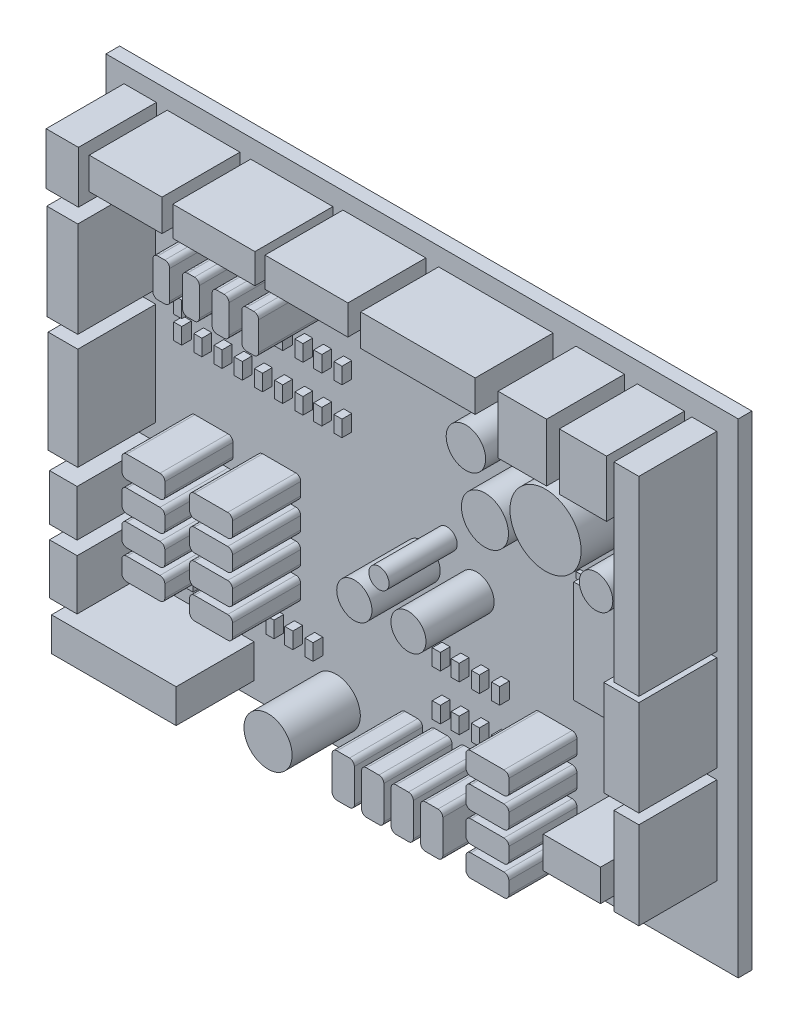
SolidWorks part; units mm, degrees
ref_plane "Plan de face" through (0, 0, 0) normal (0, 0, 1) x (1, 0, 0)
ref_plane "Plan de dessus" through (0, 0, 0) normal (0, 1, 0) x (1, 0, 0)
ref_plane "Plan de droite" through (0, 0, 0) normal (1, 0, 0) x (0, 0, -1)
sketch "Esquisse1" plane through (0, 0, 0) normal (0, 0, 1) x (1, 0, 0)
  line L1 (0, 0) -> (64.9, 0)
  line L2 (0, 0) -> (0, 49.7)
  line L3 (0, 49.7) -> (64.9, 49.7)
  line L4 (64.9, 0) -> (64.9, 49.7)
  dimension "D1" = 64.9
  dimension "D2" = 49.7
extrude "Extrusion1" add sketch "Esquisse1" along normal blind 1.4
sketch "Esquisse2" plane through (0, 0, 1.4) normal (0, 0, 1) x (1, 0, 0)
  line L1 (1.8564, 47.9767) -> (5.175, 47.9767)
  line L2 (1.8564, 47.9767) -> (1.8564, 42.6531)
  line L3 (1.8564, 42.6531) -> (5.175, 42.6531)
  line L4 (5.175, 47.9767) -> (5.175, 42.6531)
  line L5 (24.3263, 47.9767) -> (32.8303, 47.9767)
  line L6 (24.3263, 47.9767) -> (24.3263, 44.9346)
  line L7 (24.3263, 44.9346) -> (32.8303, 44.9346)
  line L8 (32.8303, 47.9767) -> (32.8303, 44.9346)
extrude "Extrusion2" add sketch "Esquisse2" along normal blind 8
sketch "Esquisse3" plane through (0, 0, 1.4) normal (0, 0, 1) x (1, 0, 0)
  line L1 (6.2812, 47.8384) -> (13.7481, 47.8384)
  line L2 (6.2812, 47.8384) -> (6.2812, 44.5889)
  line L3 (6.2812, 44.5889) -> (13.7481, 44.5889)
  line L4 (13.7481, 47.8384) -> (13.7481, 44.5889)
  line L5 (1.9255, 41.132) -> (5.1059, 41.132)
  line L6 (1.9255, 41.132) -> (1.9255, 31.3144)
  line L7 (1.9255, 31.3144) -> (5.1059, 31.3144)
  line L8 (5.1059, 41.132) -> (5.1059, 31.3144)
  line L9 (34.1439, 47.8384) -> (45.8974, 47.8384)
  line L10 (34.1439, 47.8384) -> (34.1439, 44.5889)
  line L11 (34.1439, 44.5889) -> (45.8974, 44.5889)
  line L12 (45.8974, 47.8384) -> (45.8974, 44.5889)
  line L13 (48.2481, 47.8384) -> (53.226, 47.8384)
  line L14 (48.2481, 47.8384) -> (48.2481, 41.8926)
  line L15 (48.2481, 41.8926) -> (53.226, 41.8926)
  line L16 (53.226, 47.8384) -> (53.226, 41.8926)
extrude "Extrusion3" add sketch "Esquisse3" along normal blind 8
sketch "Esquisse4" plane through (0, 0, 1.4) normal (0, 0, 1) x (1, 0, 0)
  line L1 (14.8543, 47.7693) -> (23.2892, 47.7693)
  line L2 (14.8543, 47.7693) -> (14.8543, 44.7272)
  line L3 (14.8543, 44.7272) -> (23.2892, 44.7272)
  line L4 (23.2892, 47.7693) -> (23.2892, 44.7272)
  line L5 (2.0638, 30.0008) -> (5.1059, 30.0008)
  line L6 (2.0638, 30.0008) -> (2.0638, 19.4918)
  line L7 (2.0638, 19.4918) -> (5.1059, 19.4918)
  line L8 (5.1059, 30.0008) -> (5.1059, 19.4918)
  line L9 (59.1028, 17.5559) -> (62.6979, 17.5559)
  line L10 (59.1028, 17.5559) -> (59.1028, 27.3735)
  line L11 (59.1028, 27.3735) -> (62.6979, 27.3735)
  line L12 (62.6979, 17.5559) -> (62.6979, 27.3735)
extrude "Extrusion4" add sketch "Esquisse4" along normal blind 8
sketch "Esquisse5" plane through (0, 0, 1.4) normal (0, 0, 1) x (1, 0, 0)
  line L1 (2.2021, 17.7633) -> (5.0367, 17.7633)
  line L2 (2.2021, 17.7633) -> (2.2021, 12.9928)
  line L3 (2.2021, 12.9928) -> (5.0367, 12.9928)
  line L4 (5.0367, 17.7633) -> (5.0367, 12.9928)
  line L5 (54.5396, 47.631) -> (59.3793, 47.631)
  line L6 (54.5396, 47.631) -> (54.5396, 41.8234)
  line L7 (54.5396, 41.8234) -> (59.3793, 41.8234)
  line L8 (59.3793, 47.631) -> (59.3793, 41.8234)
extrude "Extrusion5" add sketch "Esquisse5" along normal blind 8
sketch "Esquisse6" plane through (0, 0, 1.4) normal (0, 0, 1) x (1, 0, 0)
  line L1 (2.2021, 11.61) -> (5.0367, 11.61)
  line L2 (2.2021, 11.61) -> (2.2021, 6.4247)
  line L3 (2.2021, 6.4247) -> (5.0367, 6.4247)
  line L4 (5.0367, 11.61) -> (5.0367, 6.4247)
extrude "Extrusion6" add sketch "Esquisse6" along normal blind 8
sketch "Esquisse7" plane through (0, 0, 1.4) normal (0, 0, 1) x (1, 0, 0)
  line L1 (60.1398, 47.4928) -> (62.6979, 47.4928)
  line L2 (60.1398, 47.4928) -> (60.1398, 27.9266)
  line L3 (60.1398, 27.9266) -> (62.6979, 27.9266)
  line L4 (62.6979, 47.4928) -> (62.6979, 27.9266)
  line L5 (62.6979, 16.5189) -> (60.1398, 16.5189)
  line L6 (62.6979, 16.5189) -> (62.6979, 7.5309)
  line L7 (62.6979, 7.5309) -> (60.1398, 7.5309)
  line L8 (60.1398, 16.5189) -> (60.1398, 7.5309)
  line L9 (58.7571, 10.7804) -> (52.8803, 10.7804)
  line L10 (58.7571, 10.7804) -> (58.7571, 7.5309)
  line L11 (58.7571, 7.5309) -> (52.8803, 7.5309)
  line L12 (52.8803, 10.7804) -> (52.8803, 7.5309)
  line L13 (2.4095, 5.0419) -> (15.2, 5.0419)
  line L14 (2.4095, 5.0419) -> (2.4095, 1.585)
  line L15 (2.4095, 1.585) -> (15.2, 1.585)
  line L16 (15.2, 5.0419) -> (15.2, 1.585)
extrude "Extrusion7" add sketch "Esquisse7" along normal blind 8
sketch "Esquisse8" plane through (0, 0, 1.4) normal (0, 0, 1) x (1, 0, 0)
  line L0 (15.3543, 41.3926) -> (16.0828, 41.3926)
  line L1 (12.3123, 41.3926) -> (13.0407, 41.3926)
  line L2 (11.8123, 40.8926) -> (11.8123, 37.9837)
  line L3 (12.3123, 37.4837) -> (13.0407, 37.4837)
  line L4 (13.5407, 40.8926) -> (13.5407, 37.9837)
  line L5 (15.3543, 37.4837) -> (16.0828, 37.4837)
  line L6 (14.8543, 40.8926) -> (14.8543, 37.9837)
  line L7 (16.5828, 40.8926) -> (16.5828, 37.9837)
  line L8 (18.3964, 41.3926) -> (19.1249, 41.3926)
  line L9 (18.3964, 37.4837) -> (19.1249, 37.4837)
  line L10 (17.8964, 40.8926) -> (17.8964, 37.9837)
  line L11 (19.6249, 40.8926) -> (19.6249, 37.9837)
  line L12 (21.4385, 41.3926) -> (22.1669, 41.3926)
  line L13 (21.4385, 37.4837) -> (22.1669, 37.4837)
  line L14 (20.9385, 40.8926) -> (20.9385, 37.9837)
  line L15 (22.6669, 40.8926) -> (22.6669, 37.9837)
  line L16 (8.6319, 18.6621) -> (8.6319, 17.3806)
  line L17 (9.1319, 22.1882) -> (12.5407, 22.1882)
  line L18 (8.6319, 21.6882) -> (8.6319, 20.4066)
  line L19 (9.1319, 19.9066) -> (12.5407, 19.9066)
  line L20 (13.0407, 21.6882) -> (13.0407, 20.4066)
  line L21 (9.1319, 19.1621) -> (12.5407, 19.1621)
  line L22 (9.1319, 16.8806) -> (12.5407, 16.8806)
  line L23 (13.0407, 18.6621) -> (13.0407, 17.3806)
  line L24 (8.6319, 15.6361) -> (8.6319, 14.3545)
  line L25 (9.1319, 16.1361) -> (12.5407, 16.1361)
  line L26 (9.1319, 13.8545) -> (12.5407, 13.8545)
  line L27 (13.0407, 15.6361) -> (13.0407, 14.3545)
  line L28 (8.6319, 12.61) -> (8.6319, 11.3285)
  line L29 (9.1319, 13.11) -> (12.5407, 13.11)
  line L30 (9.1319, 10.8285) -> (12.5407, 10.8285)
  line L31 (13.0407, 12.61) -> (13.0407, 11.3285)
  line L32 (16.0828, 19.1621) -> (19.4916, 19.1621)
  line L33 (16.0828, 13.11) -> (19.4916, 13.11)
  line L34 (19.9916, 21.6882) -> (19.9916, 20.4066)
  line L35 (16.0828, 16.8806) -> (19.4916, 16.8806)
  line L36 (16.0828, 10.8285) -> (19.4916, 10.8285)
  line L37 (15.5828, 21.6882) -> (15.5828, 20.4066)
  line L38 (15.5828, 12.61) -> (15.5828, 11.3285)
  line L39 (19.9916, 12.61) -> (19.9916, 11.3285)
  line L40 (15.5828, 18.6621) -> (15.5828, 17.3806)
  line L41 (15.5828, 15.6361) -> (15.5828, 14.3545)
  line L42 (16.0828, 16.1361) -> (19.4916, 16.1361)
  line L43 (16.0828, 13.8545) -> (19.4916, 13.8545)
  line L44 (16.0828, 19.9066) -> (19.4916, 19.9066)
  line L45 (19.9916, 15.6361) -> (19.9916, 14.3545)
  line L46 (16.0828, 22.1882) -> (19.4916, 22.1882)
  line L47 (19.9916, 18.6621) -> (19.9916, 17.3806)
  line L48 (33.2391, 2.6942) -> (33.2391, 6.103)
  line L49 (39.2912, 2.6942) -> (39.2912, 6.103)
  line L50 (30.713, 6.603) -> (31.9946, 6.603)
  line L51 (35.5206, 2.6942) -> (35.5206, 6.103)
  line L52 (41.5727, 2.6942) -> (41.5727, 6.103)
  line L53 (30.713, 2.1942) -> (31.9946, 2.1942)
  line L54 (39.7912, 2.1942) -> (41.0727, 2.1942)
  line L55 (39.7912, 6.603) -> (41.0727, 6.603)
  line L56 (33.7391, 2.1942) -> (35.0206, 2.1942)
  line L57 (36.7651, 2.1942) -> (38.0467, 2.1942)
  line L58 (36.2651, 2.6942) -> (36.2651, 6.103)
  line L59 (38.5467, 2.6942) -> (38.5467, 6.103)
  line L60 (32.4946, 2.6942) -> (32.4946, 6.103)
  line L61 (36.7651, 6.603) -> (38.0467, 6.603)
  line L62 (30.213, 2.6942) -> (30.213, 6.103)
  line L63 (33.7391, 6.603) -> (35.0206, 6.603)
  line L64 (44.4455, 10.4507) -> (47.8543, 10.4507)
  line L65 (44.4455, 4.3986) -> (47.8543, 4.3986)
  line L66 (48.3543, 12.9768) -> (48.3543, 11.6952)
  line L67 (44.4455, 8.1692) -> (47.8543, 8.1692)
  line L68 (44.4455, 2.1171) -> (47.8543, 2.1171)
  line L69 (43.9455, 12.9768) -> (43.9455, 11.6952)
  line L70 (43.9455, 3.8986) -> (43.9455, 2.6171)
  line L71 (48.3543, 3.8986) -> (48.3543, 2.6171)
  line L72 (43.9455, 9.9507) -> (43.9455, 8.6692)
  line L73 (43.9455, 6.9247) -> (43.9455, 5.6431)
  line L74 (44.4455, 7.4247) -> (47.8543, 7.4247)
  line L75 (44.4455, 5.1431) -> (47.8543, 5.1431)
  line L76 (44.4455, 11.1952) -> (47.8543, 11.1952)
  line L77 (48.3543, 6.9247) -> (48.3543, 5.6431)
  line L78 (44.4455, 13.4768) -> (47.8543, 13.4768)
  line L79 (48.3543, 9.9507) -> (48.3543, 8.6692)
  arc A0 (12.3123, 41.3926) -> (11.8123, 40.8926) centre (12.3123, 40.8926) ccw
  arc A1 (13.0407, 41.3926) -> (13.5407, 40.8926) centre (13.0407, 40.8926) cw
  arc A2 (13.0407, 37.4837) -> (13.5407, 37.9837) centre (13.0407, 37.9837) ccw
  arc A3 (11.8123, 37.9837) -> (12.3123, 37.4837) centre (12.3123, 37.9837) ccw
  arc A4 (14.8543, 37.9837) -> (15.3543, 37.4837) centre (15.3543, 37.9837) ccw
  arc A5 (15.3543, 41.3926) -> (14.8543, 40.8926) centre (15.3543, 40.8926) ccw
  arc A6 (16.0828, 41.3926) -> (16.5828, 40.8926) centre (16.0828, 40.8926) cw
  arc A7 (16.0828, 37.4837) -> (16.5828, 37.9837) centre (16.0828, 37.9837) ccw
  arc A8 (17.8964, 37.9837) -> (18.3964, 37.4837) centre (18.3964, 37.9837) ccw
  arc A9 (18.3964, 41.3926) -> (17.8964, 40.8926) centre (18.3964, 40.8926) ccw
  arc A10 (19.1249, 41.3926) -> (19.6249, 40.8926) centre (19.1249, 40.8926) cw
  arc A11 (19.1249, 37.4837) -> (19.6249, 37.9837) centre (19.1249, 37.9837) ccw
  arc A12 (20.9385, 37.9837) -> (21.4385, 37.4837) centre (21.4385, 37.9837) ccw
  arc A13 (21.4385, 41.3926) -> (20.9385, 40.8926) centre (21.4385, 40.8926) ccw
  arc A14 (22.1669, 41.3926) -> (22.6669, 40.8926) centre (22.1669, 40.8926) cw
  arc A15 (22.1669, 37.4837) -> (22.6669, 37.9837) centre (22.1669, 37.9837) ccw
  arc A16 (9.1319, 22.1882) -> (8.6319, 21.6882) centre (9.1319, 21.6882) ccw
  arc A17 (8.6319, 20.4066) -> (9.1319, 19.9066) centre (9.1319, 20.4066) ccw
  arc A18 (12.5407, 19.9066) -> (13.0407, 20.4066) centre (12.5407, 20.4066) ccw
  arc A19 (12.5407, 22.1882) -> (13.0407, 21.6882) centre (12.5407, 21.6882) cw
  arc A20 (8.6319, 17.3806) -> (9.1319, 16.8806) centre (9.1319, 17.3806) ccw
  arc A21 (12.5407, 19.1621) -> (13.0407, 18.6621) centre (12.5407, 18.6621) cw
  arc A22 (12.5407, 16.8806) -> (13.0407, 17.3806) centre (12.5407, 17.3806) ccw
  arc A23 (9.1319, 19.1621) -> (8.6319, 18.6621) centre (9.1319, 18.6621) ccw
  arc A24 (8.6319, 14.3545) -> (9.1319, 13.8545) centre (9.1319, 14.3545) ccw
  arc A25 (12.5407, 16.1361) -> (13.0407, 15.6361) centre (12.5407, 15.6361) cw
  arc A26 (12.5407, 13.8545) -> (13.0407, 14.3545) centre (12.5407, 14.3545) ccw
  arc A27 (9.1319, 16.1361) -> (8.6319, 15.6361) centre (9.1319, 15.6361) ccw
  arc A28 (8.6319, 11.3285) -> (9.1319, 10.8285) centre (9.1319, 11.3285) ccw
  arc A29 (12.5407, 13.11) -> (13.0407, 12.61) centre (12.5407, 12.61) cw
  arc A30 (12.5407, 10.8285) -> (13.0407, 11.3285) centre (12.5407, 11.3285) ccw
  arc A31 (9.1319, 13.11) -> (8.6319, 12.61) centre (9.1319, 12.61) ccw
  arc A32 (16.0828, 19.1621) -> (15.5828, 18.6621) centre (16.0828, 18.6621) ccw
  arc A33 (15.5828, 20.4066) -> (16.0828, 19.9066) centre (16.0828, 20.4066) ccw
  arc A34 (15.5828, 11.3285) -> (16.0828, 10.8285) centre (16.0828, 11.3285) ccw
  arc A35 (15.5828, 14.3545) -> (16.0828, 13.8545) centre (16.0828, 14.3545) ccw
  arc A36 (19.4916, 10.8285) -> (19.9916, 11.3285) centre (19.4916, 11.3285) ccw
  arc A37 (19.4916, 13.11) -> (19.9916, 12.61) centre (19.4916, 12.61) cw
  arc A38 (16.0828, 13.11) -> (15.5828, 12.61) centre (16.0828, 12.61) ccw
  arc A39 (19.4916, 22.1882) -> (19.9916, 21.6882) centre (19.4916, 21.6882) cw
  arc A40 (19.4916, 19.1621) -> (19.9916, 18.6621) centre (19.4916, 18.6621) cw
  arc A41 (19.4916, 16.1361) -> (19.9916, 15.6361) centre (19.4916, 15.6361) cw
  arc A42 (15.5828, 17.3806) -> (16.0828, 16.8806) centre (16.0828, 17.3806) ccw
  arc A43 (19.4916, 19.9066) -> (19.9916, 20.4066) centre (19.4916, 20.4066) ccw
  arc A44 (19.4916, 16.8806) -> (19.9916, 17.3806) centre (19.4916, 17.3806) ccw
  arc A45 (19.4916, 13.8545) -> (19.9916, 14.3545) centre (19.4916, 14.3545) ccw
  arc A46 (16.0828, 22.1882) -> (15.5828, 21.6882) centre (16.0828, 21.6882) ccw
  arc A47 (16.0828, 16.1361) -> (15.5828, 15.6361) centre (16.0828, 15.6361) ccw
  arc A48 (33.2391, 2.6942) -> (33.7391, 2.1942) centre (33.7391, 2.6942) ccw
  arc A49 (31.9946, 2.1942) -> (32.4946, 2.6942) centre (31.9946, 2.6942) ccw
  arc A50 (41.0727, 2.1942) -> (41.5727, 2.6942) centre (41.0727, 2.6942) ccw
  arc A51 (38.0467, 2.1942) -> (38.5467, 2.6942) centre (38.0467, 2.6942) ccw
  arc A52 (41.5727, 6.103) -> (41.0727, 6.603) centre (41.0727, 6.103) ccw
  arc A53 (39.2912, 6.103) -> (39.7912, 6.603) centre (39.7912, 6.103) cw
  arc A54 (39.2912, 2.6942) -> (39.7912, 2.1942) centre (39.7912, 2.6942) ccw
  arc A55 (30.213, 6.103) -> (30.713, 6.603) centre (30.713, 6.103) cw
  arc A56 (33.2391, 6.103) -> (33.7391, 6.603) centre (33.7391, 6.103) cw
  arc A57 (36.2651, 6.103) -> (36.7651, 6.603) centre (36.7651, 6.103) cw
  arc A58 (35.0206, 2.1942) -> (35.5206, 2.6942) centre (35.0206, 2.6942) ccw
  arc A59 (32.4946, 6.103) -> (31.9946, 6.603) centre (31.9946, 6.103) ccw
  arc A60 (35.5206, 6.103) -> (35.0206, 6.603) centre (35.0206, 6.103) ccw
  arc A61 (38.5467, 6.103) -> (38.0467, 6.603) centre (38.0467, 6.103) ccw
  arc A62 (30.213, 2.6942) -> (30.713, 2.1942) centre (30.713, 2.6942) ccw
  arc A63 (36.2651, 2.6942) -> (36.7651, 2.1942) centre (36.7651, 2.6942) ccw
  arc A64 (44.4455, 10.4507) -> (43.9455, 9.9507) centre (44.4455, 9.9507) ccw
  arc A65 (43.9455, 11.6952) -> (44.4455, 11.1952) centre (44.4455, 11.6952) ccw
  arc A66 (43.9455, 2.6171) -> (44.4455, 2.1171) centre (44.4455, 2.6171) ccw
  arc A67 (43.9455, 5.6431) -> (44.4455, 5.1431) centre (44.4455, 5.6431) ccw
  arc A68 (47.8543, 2.1171) -> (48.3543, 2.6171) centre (47.8543, 2.6171) ccw
  arc A69 (47.8543, 4.3986) -> (48.3543, 3.8986) centre (47.8543, 3.8986) cw
  arc A70 (44.4455, 4.3986) -> (43.9455, 3.8986) centre (44.4455, 3.8986) ccw
  arc A71 (47.8543, 13.4768) -> (48.3543, 12.9768) centre (47.8543, 12.9768) cw
  arc A72 (47.8543, 10.4507) -> (48.3543, 9.9507) centre (47.8543, 9.9507) cw
  arc A73 (47.8543, 7.4247) -> (48.3543, 6.9247) centre (47.8543, 6.9247) cw
  arc A74 (43.9455, 8.6692) -> (44.4455, 8.1692) centre (44.4455, 8.6692) ccw
  arc A75 (47.8543, 11.1952) -> (48.3543, 11.6952) centre (47.8543, 11.6952) ccw
  arc A76 (47.8543, 8.1692) -> (48.3543, 8.6692) centre (47.8543, 8.6692) ccw
  arc A77 (47.8543, 5.1431) -> (48.3543, 5.6431) centre (47.8543, 5.6431) ccw
  arc A78 (44.4455, 13.4768) -> (43.9455, 12.9768) centre (44.4455, 12.9768) ccw
  arc A79 (44.4455, 7.4247) -> (43.9455, 6.9247) centre (44.4455, 6.9247) ccw
  circle A80 centre (23.6349, 3.8986) radius 2.471
  circle A81 centre (52.1198, 36.9146) radius 3.6513
  circle A82 centre (43.9455, 40.1641) radius 2.0241
  circle A83 centre (45.8974, 34.7022) radius 2.4149
  circle A84 centre (57.3052, 34.0799) radius 1.7174
  circle A85 centre (35.0206, 24.124) radius 1.0371
  circle A86 centre (32.4946, 20.8746) radius 1.8095
  circle A87 centre (38.0467, 20.8746) radius 1.7976
  dimension "D1" = 0.5
  dimension "D2" = 0.5
extrude "Extrusion8" add sketch "Esquisse8" along normal blind 7
sketch "Esquisse9" plane through (0, 0, 1.4) normal (0, 0, 1) x (1, 0, 0)
  line L1 (50.0109, 28.7674) -> (55.9868, 28.7674)
  line L2 (50.0109, 28.7674) -> (50.0109, 18.2549)
  line L3 (50.0109, 18.2549) -> (55.9868, 18.2549)
  line L4 (55.9868, 28.7674) -> (55.9868, 18.2549)
extrude "Extrusion9" add sketch "Esquisse9" along normal blind 2
sketch "Esquisse10" plane through (0, 0, 1.4) normal (0, 0, 1) x (1, 0, 0)
  line L0 (50.0109, 28.7674) -> (50.0109, 18.2549) construction
  line L1 (50.0109, 28.2032) -> (48.6629, 28.2032)
  line L2 (50.0109, 28.2032) -> (50.0109, 27.581)
  line L3 (50.0109, 27.581) -> (48.6629, 27.581)
  line L4 (48.6629, 28.2032) -> (48.6629, 27.581)
  line L5 (50.0109, 26.8204) -> (50.0109, 26.1982)
  line L6 (50.0109, 26.8204) -> (48.6629, 26.8204)
  line L7 (48.6629, 26.8204) -> (48.6629, 26.1982)
  line L8 (50.0109, 26.1982) -> (48.6629, 26.1982)
  line L9 (50.0109, 25.4377) -> (50.0109, 24.8154)
  line L10 (50.0109, 25.4377) -> (48.6629, 25.4377)
  line L11 (48.6629, 25.4377) -> (48.6629, 24.8154)
  line L12 (50.0109, 24.8154) -> (48.6629, 24.8154)
  line L13 (50.0109, 24.0549) -> (50.0109, 23.4327)
  line L14 (50.0109, 24.0549) -> (48.6629, 24.0549)
  line L15 (48.6629, 24.0549) -> (48.6629, 23.4327)
  line L16 (50.0109, 23.4327) -> (48.6629, 23.4327)
  line L17 (50.0109, 22.6721) -> (50.0109, 22.0499)
  line L18 (50.0109, 22.6721) -> (48.6629, 22.6721)
  line L19 (48.6629, 22.6721) -> (48.6629, 22.0499)
  line L20 (50.0109, 22.0499) -> (48.6629, 22.0499)
  line L21 (50.0109, 21.2894) -> (50.0109, 20.6671)
  line L22 (50.0109, 21.2894) -> (48.6629, 21.2894)
  line L23 (48.6629, 21.2894) -> (48.6629, 20.6671)
  line L24 (50.0109, 20.6671) -> (48.6629, 20.6671)
  line L25 (50.0109, 19.9066) -> (50.0109, 19.2844)
  line L26 (50.0109, 19.9066) -> (48.6629, 19.9066)
  line L27 (48.6629, 19.9066) -> (48.6629, 19.2844)
  line L28 (50.0109, 19.2844) -> (48.6629, 19.2844)
  line L29 (52.9988, 28.7674) -> (52.9988, 15.7583) construction
  line L30 (55.9868, 28.7674) -> (50.0109, 28.7674) construction
  line L31 (55.9868, 19.2844) -> (57.3347, 19.2844)
  line L32 (57.3347, 19.9066) -> (57.3347, 19.2844)
  line L33 (55.9868, 19.9066) -> (57.3347, 19.9066)
  line L34 (55.9868, 19.9066) -> (55.9868, 19.2844)
  line L35 (55.9868, 20.6671) -> (57.3347, 20.6671)
  line L36 (57.3347, 21.2894) -> (57.3347, 20.6671)
  line L37 (55.9868, 21.2894) -> (57.3347, 21.2894)
  line L38 (55.9868, 21.2894) -> (55.9868, 20.6671)
  line L39 (55.9868, 22.0499) -> (57.3347, 22.0499)
  line L40 (57.3347, 22.6721) -> (57.3347, 22.0499)
  line L41 (55.9868, 22.6721) -> (57.3347, 22.6721)
  line L42 (55.9868, 22.6721) -> (55.9868, 22.0499)
  line L43 (55.9868, 23.4327) -> (57.3347, 23.4327)
  line L44 (57.3347, 24.0549) -> (57.3347, 23.4327)
  line L45 (55.9868, 24.0549) -> (57.3347, 24.0549)
  line L46 (55.9868, 24.0549) -> (55.9868, 23.4327)
  line L47 (55.9868, 24.8154) -> (57.3347, 24.8154)
  line L48 (57.3347, 25.4377) -> (57.3347, 24.8154)
  line L49 (55.9868, 25.4377) -> (57.3347, 25.4377)
  line L50 (55.9868, 25.4377) -> (55.9868, 24.8154)
  line L51 (55.9868, 26.1982) -> (57.3347, 26.1982)
  line L52 (57.3347, 26.8204) -> (57.3347, 26.1982)
  line L53 (55.9868, 26.8204) -> (57.3347, 26.8204)
  line L54 (55.9868, 26.8204) -> (55.9868, 26.1982)
  line L55 (57.3347, 28.2032) -> (57.3347, 27.581)
  line L56 (55.9868, 27.581) -> (57.3347, 27.581)
  line L57 (55.9868, 28.2032) -> (55.9868, 27.581)
  line L58 (55.9868, 28.2032) -> (57.3347, 28.2032)
extrude "Extrusion10" add sketch "Esquisse10" along normal blind 0.4
sketch "Esquisse11" plane through (0, 0, 1.4) normal (0, 0, 1) x (1, 0, 0)
  line L0 (10.8443, 35.0479) -> (10.8443, 33.3886)
  line L1 (7.9405, 35.0479) -> (8.7702, 35.0479)
  line L2 (7.9405, 35.0479) -> (7.9405, 33.3886)
  line L3 (7.9405, 33.3886) -> (8.7702, 33.3886)
  line L4 (8.7702, 35.0479) -> (8.7702, 33.3886)
  line L5 (10.0147, 35.0479) -> (10.8443, 35.0479)
  line L6 (10.0147, 35.0479) -> (10.0147, 33.3886)
  line L7 (10.0147, 33.3886) -> (10.8443, 33.3886)
  line L8 (12.9185, 35.0479) -> (12.9185, 33.3886)
  line L9 (12.0888, 35.0479) -> (12.9185, 35.0479)
  line L10 (12.0888, 35.0479) -> (12.0888, 33.3886)
  line L11 (12.0888, 33.3886) -> (12.9185, 33.3886)
  line L12 (14.9926, 35.0479) -> (14.9926, 33.3886)
  line L13 (14.163, 35.0479) -> (14.9926, 35.0479)
  line L14 (14.163, 35.0479) -> (14.163, 33.3886)
  line L15 (14.163, 33.3886) -> (14.9926, 33.3886)
  line L16 (17.0668, 35.0479) -> (17.0668, 33.3886)
  line L17 (16.2371, 35.0479) -> (17.0668, 35.0479)
  line L18 (16.2371, 35.0479) -> (16.2371, 33.3886)
  line L19 (16.2371, 33.3886) -> (17.0668, 33.3886)
  line L20 (19.1409, 35.0479) -> (19.1409, 33.3886)
  line L21 (18.3112, 35.0479) -> (19.1409, 35.0479)
  line L22 (18.3112, 35.0479) -> (18.3112, 33.3886)
  line L23 (18.3112, 33.3886) -> (19.1409, 33.3886)
  line L24 (21.215, 35.0479) -> (21.215, 33.3886)
  line L25 (20.3854, 35.0479) -> (21.215, 35.0479)
  line L26 (20.3854, 35.0479) -> (20.3854, 33.3886)
  line L27 (20.3854, 33.3886) -> (21.215, 33.3886)
  line L28 (8.7702, 32.6972) -> (8.7702, 31.0379)
  line L29 (7.9405, 32.6972) -> (8.7702, 32.6972)
  line L30 (7.9405, 32.6972) -> (7.9405, 31.0379)
  line L31 (7.9405, 31.0379) -> (8.7702, 31.0379)
  line L32 (8.7702, 30.3465) -> (8.7702, 28.6872)
  line L33 (7.9405, 30.3465) -> (8.7702, 30.3465)
  line L34 (7.9405, 30.3465) -> (7.9405, 28.6872)
  line L35 (7.9405, 28.6872) -> (8.7702, 28.6872)
  line L36 (10.8443, 30.3465) -> (10.8443, 28.6872)
  line L37 (10.0147, 30.3465) -> (10.0147, 28.6872)
  line L38 (10.0147, 30.3465) -> (10.8443, 30.3465)
  line L39 (10.0147, 28.6872) -> (10.8443, 28.6872)
  line L40 (12.9185, 30.3465) -> (12.9185, 28.6872)
  line L41 (12.0888, 30.3465) -> (12.0888, 28.6872)
  line L42 (12.0888, 30.3465) -> (12.9185, 30.3465)
  line L43 (12.0888, 28.6872) -> (12.9185, 28.6872)
  line L44 (14.9926, 30.3465) -> (14.9926, 28.6872)
  line L45 (14.163, 30.3465) -> (14.163, 28.6872)
  line L46 (14.163, 30.3465) -> (14.9926, 30.3465)
  line L47 (14.163, 28.6872) -> (14.9926, 28.6872)
  line L48 (17.0668, 30.3465) -> (17.0668, 28.6872)
  line L49 (16.2371, 30.3465) -> (16.2371, 28.6872)
  line L50 (16.2371, 30.3465) -> (17.0668, 30.3465)
  line L51 (16.2371, 28.6872) -> (17.0668, 28.6872)
  line L52 (19.1409, 30.3465) -> (19.1409, 28.6872)
  line L53 (18.3112, 30.3465) -> (18.3112, 28.6872)
  line L54 (18.3112, 30.3465) -> (19.1409, 30.3465)
  line L55 (18.3112, 28.6872) -> (19.1409, 28.6872)
  line L56 (21.215, 30.3465) -> (21.215, 28.6872)
  line L57 (20.3854, 30.3465) -> (20.3854, 28.6872)
  line L58 (20.3854, 30.3465) -> (21.215, 30.3465)
  line L59 (20.3854, 28.6872) -> (21.215, 28.6872)
  line L60 (23.1509, 30.3465) -> (23.1509, 28.6872)
  line L61 (22.3213, 33.3886) -> (23.1509, 33.3886)
  line L62 (22.3213, 30.3465) -> (23.1509, 30.3465)
  line L63 (35.3192, 9.9507) -> (35.3192, 8.2914)
  line L64 (25.2251, 30.3465) -> (25.2251, 28.6872)
  line L65 (34.4896, 9.9507) -> (34.4896, 8.2914)
  line L66 (22.3213, 28.6872) -> (23.1509, 28.6872)
  line L67 (22.3213, 35.0479) -> (23.1509, 35.0479)
  line L68 (24.3954, 35.0479) -> (25.2251, 35.0479)
  line L69 (24.3954, 30.3465) -> (25.2251, 30.3465)
  line L70 (22.3213, 30.3465) -> (22.3213, 28.6872)
  line L71 (34.4896, 8.2914) -> (35.3192, 8.2914)
  line L72 (24.3954, 35.0479) -> (24.3954, 33.3886)
  line L73 (23.1509, 35.0479) -> (23.1509, 33.3886)
  line L74 (24.3954, 33.3886) -> (25.2251, 33.3886)
  line L75 (35.3192, 14.6521) -> (35.3192, 12.9928)
  line L76 (34.4896, 14.6521) -> (34.4896, 12.9928)
  line L77 (34.4896, 9.9507) -> (35.3192, 9.9507)
  line L78 (25.2251, 35.0479) -> (25.2251, 33.3886)
  line L79 (24.3954, 28.6872) -> (25.2251, 28.6872)
  line L80 (34.4896, 14.6521) -> (35.3192, 14.6521)
  line L81 (34.4896, 12.9928) -> (35.3192, 12.9928)
  line L82 (22.3213, 35.0479) -> (22.3213, 33.3886)
  line L83 (24.3954, 30.3465) -> (24.3954, 28.6872)
  line L84 (37.2551, 9.9507) -> (37.2551, 8.2914)
  line L85 (36.4254, 12.9928) -> (37.2551, 12.9928)
  line L86 (36.4254, 9.9507) -> (37.2551, 9.9507)
  line L87 (41.4034, 9.9507) -> (41.4034, 8.2914)
  line L88 (39.3292, 9.9507) -> (39.3292, 8.2914)
  line L89 (40.5737, 9.9507) -> (40.5737, 8.2914)
  line L90 (36.4254, 8.2914) -> (37.2551, 8.2914)
  line L91 (36.4254, 14.6521) -> (37.2551, 14.6521)
  line L92 (38.4996, 14.6521) -> (39.3292, 14.6521)
  line L93 (38.4996, 9.9507) -> (39.3292, 9.9507)
  line L94 (36.4254, 9.9507) -> (36.4254, 8.2914)
  line L95 (40.5737, 8.2914) -> (41.4034, 8.2914)
  line L96 (38.4996, 14.6521) -> (38.4996, 12.9928)
  line L97 (37.2551, 14.6521) -> (37.2551, 12.9928)
  line L98 (38.4996, 12.9928) -> (39.3292, 12.9928)
  line L99 (41.4034, 14.6521) -> (41.4034, 12.9928)
  line L100 (40.5737, 14.6521) -> (40.5737, 12.9928)
  line L101 (40.5737, 9.9507) -> (41.4034, 9.9507)
  line L102 (39.3292, 14.6521) -> (39.3292, 12.9928)
  line L103 (38.4996, 8.2914) -> (39.3292, 8.2914)
  line L104 (40.5737, 14.6521) -> (41.4034, 14.6521)
  line L105 (40.5737, 12.9928) -> (41.4034, 12.9928)
  line L106 (36.4254, 14.6521) -> (36.4254, 12.9928)
  line L107 (38.4996, 9.9507) -> (38.4996, 8.2914)
  line L108 (52.3272, 5.3185) -> (52.3272, 3.6592)
  line L109 (51.4976, 5.3185) -> (51.4976, 3.6592)
  line L110 (51.4976, 5.3185) -> (52.3272, 5.3185)
  line L111 (51.4976, 3.6592) -> (52.3272, 3.6592)
  line L112 (53.4334, 3.6592) -> (54.2631, 3.6592)
  line L113 (53.4334, 5.3185) -> (54.2631, 5.3185)
  line L114 (55.5076, 5.3185) -> (56.3372, 5.3185)
  line L115 (55.5076, 5.3185) -> (55.5076, 3.6592)
  line L116 (54.2631, 5.3185) -> (54.2631, 3.6592)
  line L117 (55.5076, 3.6592) -> (56.3372, 3.6592)
  line L118 (58.4114, 5.3185) -> (58.4114, 3.6592)
  line L119 (57.5817, 5.3185) -> (57.5817, 3.6592)
  line L120 (56.3372, 5.3185) -> (56.3372, 3.6592)
  line L121 (57.5817, 5.3185) -> (58.4114, 5.3185)
  line L122 (57.5817, 3.6592) -> (58.4114, 3.6592)
  line L123 (53.4334, 5.3185) -> (53.4334, 3.6592)
  line L124 (9.9455, 8.9828) -> (9.9455, 7.3235)
  line L125 (9.1159, 8.9828) -> (9.1159, 7.3235)
  line L126 (9.1159, 8.9828) -> (9.9455, 8.9828)
  line L127 (9.1159, 7.3235) -> (9.9455, 7.3235)
  line L128 (12.0197, 8.9828) -> (12.0197, 7.3235)
  line L129 (11.19, 8.9828) -> (11.19, 7.3235)
  line L130 (11.19, 8.9828) -> (12.0197, 8.9828)
  line L131 (11.19, 7.3235) -> (12.0197, 7.3235)
  line L132 (14.0938, 8.9828) -> (14.0938, 7.3235)
  line L133 (13.2642, 8.9828) -> (13.2642, 7.3235)
  line L134 (13.2642, 8.9828) -> (14.0938, 8.9828)
  line L135 (13.2642, 7.3235) -> (14.0938, 7.3235)
  line L136 (16.168, 8.9828) -> (16.168, 7.3235)
  line L137 (15.3383, 8.9828) -> (15.3383, 7.3235)
  line L138 (15.3383, 8.9828) -> (16.168, 8.9828)
  line L139 (15.3383, 7.3235) -> (16.168, 7.3235)
  line L140 (18.2421, 8.9828) -> (18.2421, 7.3235)
  line L141 (17.4124, 8.9828) -> (17.4124, 7.3235)
  line L142 (17.4124, 8.9828) -> (18.2421, 8.9828)
  line L143 (17.4124, 7.3235) -> (18.2421, 7.3235)
  line L144 (20.178, 8.9828) -> (20.178, 7.3235)
  line L145 (19.3483, 8.9828) -> (20.178, 8.9828)
  line L146 (22.2521, 8.9828) -> (22.2521, 7.3235)
  line L147 (19.3483, 7.3235) -> (20.178, 7.3235)
  line L148 (21.4225, 8.9828) -> (22.2521, 8.9828)
  line L149 (19.3483, 8.9828) -> (19.3483, 7.3235)
  line L150 (21.4225, 7.3235) -> (22.2521, 7.3235)
  line L151 (21.4225, 8.9828) -> (21.4225, 7.3235)
extrude "Extrusion11" add sketch "Esquisse11" along normal blind 1
